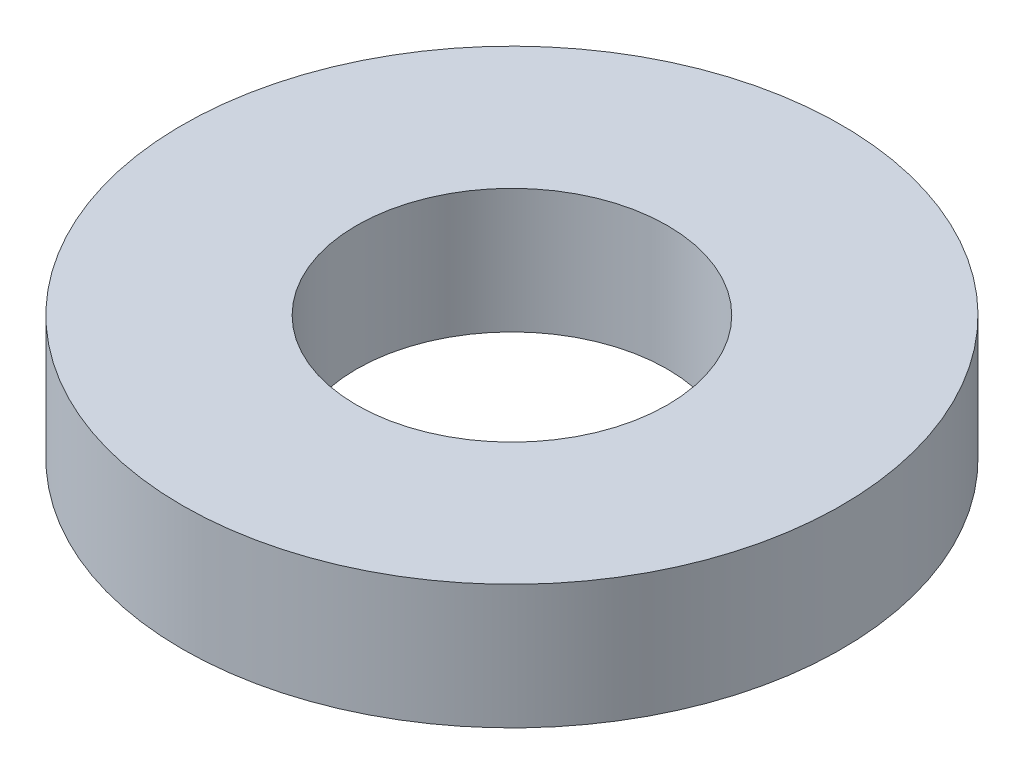
SolidWorks part; units mm, degrees
ref_plane "Front Plane" through (0, 0, 0) normal (0, 0, 1) x (1, 0, 0)
ref_plane "Top Plane" through (0, 0, 0) normal (0, 1, 0) x (1, 0, 0)
ref_plane "Right Plane" through (0, 0, 0) normal (1, 0, 0) x (0, 0, -1)
sketch "Sketch1" plane through (0, 0, 0) normal (0, 1, 0) x (1, 0, 0)
  circle A0 centre (0, 0) radius 6.731
  dimension "D1" = 13.462
extrude "Boss-Extrude1" add sketch "Sketch1" along normal blind 2.54
hole_wizard "1/4 (0.25) Diameter Hole1" positions "Sketch2" profile "Sketch3" hole size "1/4" standard "ANSI Inch" end condition through all
sketch "Sketch2" plane through (0, 2.54, 0) normal (0, 1, 0) x (1, 0, 0)
  point P0 (0, 0)
sketch "Sketch3" plane through (0, 2.54, 0) normal (1, 0, 0) x (0, 0, 1)
  line L0 (0, 0) -> (0, 2.54)
  line L1 (0, 2.54) -> (3.175, 2.54)
  line L2 (3.175, 2.54) -> (3.175, 0)
  line L5 (3.175, 0) -> (0, 0)
  line L11 (0, -6.35) -> (0, 107.95) construction
  dimension "Thru Hole Dia." = 6.35
  dimension "Thru Hole Depth" = 2.54
